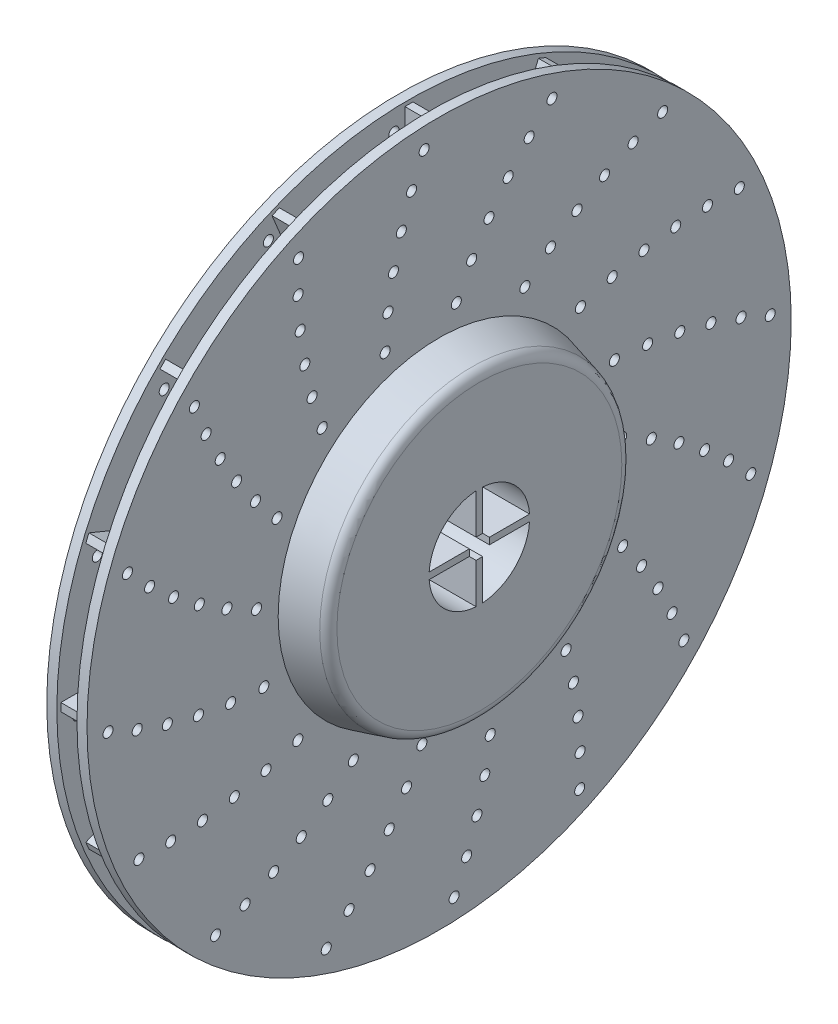
SolidWorks part; units mm, degrees
material "AISI 1020"
ref_plane "Ön Düzlem" through (0, 0, 0) normal (0, 0, 1) x (1, 0, 0)
ref_plane "Üst Düzlem" through (0, 0, 0) normal (0, 1, 0) x (1, 0, 0)
ref_plane "Sağ Düzlem" through (0, 0, 0) normal (1, 0, 0) x (0, 0, -1)
sketch "Çizim2" plane through (0, 0, 0) normal (1, 0, 0) x (0, 0, -1)
  line L0 (0.8201, 2.5) -> (0.8201, 12.4731)
  line L1 (12.4731, 0.8201) -> (2.5, 0.8201)
  line L2 (-0.8201, 12.4731) -> (-0.8201, 2.5)
  line L3 (-2.5, 0.8201) -> (-12.4731, 0.8201)
  line L4 (-12.4731, -0.8201) -> (-2.5, -0.8201)
  line L5 (-0.8201, -2.5) -> (-0.8201, -12.4731)
  line L6 (0.8201, -12.4731) -> (0.8201, -2.5)
  line L7 (2.5, -0.8201) -> (12.4731, -0.8201)
  line L8 (0, 0) -> (0.8201, 0.8201) construction
  line L9 (-0.8201, 2.5) -> (0.8201, 2.5)
  line L10 (-2.5, 0.8201) -> (-2.5, -0.8201)
  line L11 (-0.8201, -2.5) -> (0.8201, -2.5)
  line L12 (2.5, 0.8201) -> (2.5, -0.8201)
  line L13 (0, 0) -> (0.8201, -0.8201) construction
  arc A4 (-12.4731, 0.8201) -> (-12.4731, -0.8201) centre (0, 0) ccw
  arc A5 (-0.8201, -12.4731) -> (0.8201, -12.4731) centre (0, 0) ccw
  arc A6 (12.4731, -0.8201) -> (12.4731, 0.8201) centre (0, 0) ccw
  arc A7 (0.8201, 12.4731) -> (-0.8201, 12.4731) centre (0, 0) ccw
extrude "Yükseklik-Ekstrüzyon1" add sketch "Çizim2" along normal blind 30
sketch "Çizim3" plane through (0, 0, 0) normal (1, 0, 0) x (0, 0, -1)
  circle A0 centre (0, 0) radius 12.5
  circle A1 centre (0, 0) radius 25
  dimension "D1" = 25
  dimension "D2" = 50
extrude "Yükseklik-Ekstrüzyon2" add sketch "Çizim3" along normal blind 30
sketch "Çizim4" plane through (30, 0, 0) normal (1, 0, 0) x (0, 0, -1)
  circle A0 centre (0, 0) radius 25
  circle A1 centre (0, 0) radius 87.5
  dimension "D1" = 175
extrude "Yükseklik-Ekstrüzyon5" add sketch "Çizim4" against normal blind 10 from offset 10 offset against normal yes
ref_plane "Düzlem1" through (15, 0, 0) normal (1, 0, 0) x (0, 0, -1)
sketch "Çizim9" plane through (15, 0, 0) normal (1, 0, 0) x (0, 0, -1)
  circle A0 centre (0, 0) radius 37.5
  circle A1 centre (0, 0) radius 87.5
  dimension "D1" = 75
extrude "Kes-Ekstrüzyon1" cut sketch "Çizim9" against normal mid plane 5
sketch "Çizim10" plane through (15, 0, 0) normal (1, 0, 0) x (0, 0, -1)
  line L0 (0, 37.5) -> (0, 85) construction
  line L1 (1, 37.4867) -> (1, 86.4942)
  line L2 (-1, 37.4867) -> (-1, 86.4942)
  line L5 (-2.5, 35.9131) -> (-2.5, 86.4639) construction
  line L6 (2.5, 35.9131) -> (2.5, 86.4639) construction
  line L7 (-1, 37.4867) -> (-1, 84.9941) construction
  line L8 (1, 37.4867) -> (1, 84.9941) construction
  line L9 (15.2694, 34.2505) -> (34.0238, 79.5276)
  line L10 (13.4216, 35.0158) -> (32.176, 80.2929)
  line L11 (14.3506, 34.6455) -> (32.5281, 78.5298) construction
  line L12 (27.2142, 25.8) -> (61.8678, 60.4535)
  line L13 (25.8, 27.2142) -> (60.4535, 61.8678)
  line L14 (26.5165, 26.5165) -> (60.1041, 60.1041) construction
  line L15 (35.0158, 13.4216) -> (80.2929, 32.176)
  line L16 (34.2505, 15.2694) -> (79.5276, 34.0238)
  line L17 (34.6455, 14.3506) -> (78.5298, 32.5281) construction
  line L18 (37.4867, -1) -> (86.4942, -1)
  line L19 (37.4867, 1) -> (86.4942, 1)
  line L20 (37.5, 0) -> (85, 0) construction
  line L21 (34.2505, -15.2694) -> (79.5276, -34.0238)
  line L22 (35.0158, -13.4216) -> (80.2929, -32.176)
  line L23 (34.6455, -14.3506) -> (78.5298, -32.5281) construction
  line L24 (25.8, -27.2142) -> (60.4535, -61.8678)
  line L25 (27.2142, -25.8) -> (61.8678, -60.4535)
  line L26 (26.5165, -26.5165) -> (60.1041, -60.1041) construction
  line L27 (13.4216, -35.0158) -> (32.176, -80.2929)
  line L28 (15.2694, -34.2505) -> (34.0238, -79.5276)
  line L29 (14.3506, -34.6455) -> (32.5281, -78.5298) construction
  line L30 (-1, -37.4867) -> (-1, -86.4942)
  line L31 (1, -37.4867) -> (1, -86.4942)
  line L32 (0, -37.5) -> (0, -85) construction
  line L33 (-15.2694, -34.2505) -> (-34.0238, -79.5276)
  line L34 (-13.4216, -35.0158) -> (-32.176, -80.2929)
  line L35 (-14.3506, -34.6455) -> (-32.5281, -78.5298) construction
  line L36 (-27.2142, -25.8) -> (-61.8678, -60.4535)
  line L37 (-25.8, -27.2142) -> (-60.4535, -61.8678)
  line L38 (-26.5165, -26.5165) -> (-60.1041, -60.1041) construction
  line L39 (-35.0158, -13.4216) -> (-80.2929, -32.176)
  line L40 (-34.2505, -15.2694) -> (-79.5276, -34.0238)
  line L41 (-34.6455, -14.3506) -> (-78.5298, -32.5281) construction
  line L42 (-37.4867, 1) -> (-86.4942, 1)
  line L43 (-37.4867, -1) -> (-86.4942, -1)
  line L44 (-37.5, 0) -> (-85, 0) construction
  line L45 (-34.2505, 15.2694) -> (-79.5276, 34.0238)
  line L46 (-35.0158, 13.4216) -> (-80.2929, 32.176)
  line L47 (-34.6455, 14.3506) -> (-78.5298, 32.5281) construction
  line L48 (-25.8, 27.2142) -> (-60.4535, 61.8678)
  line L49 (-27.2142, 25.8) -> (-61.8678, 60.4535)
  line L50 (-26.5165, 26.5165) -> (-60.1041, 60.1041) construction
  line L51 (-13.4216, 35.0158) -> (-32.176, 80.2929)
  line L52 (-15.2694, 34.2505) -> (-34.0238, 79.5276)
  line L53 (-14.3506, 34.6455) -> (-32.5281, 78.5298) construction
  arc A0 (1, 37.4867) -> (-1, 37.4867) centre (0, 0) ccw
  arc A3 (1, 86.4942) -> (-1, 86.4942) centre (0, 0) ccw
  arc A5 (2.5, 35.9131) -> (-2.5, 35.9131) centre (0, 0) ccw construction
  arc A6 (1, 84.9941) -> (-1, 84.9941) centre (0, 0) ccw construction
  arc A7 (2.5, 86.4639) -> (-2.5, 86.4639) centre (0, 0) ccw construction
  arc A8 (15.2694, 34.2505) -> (13.4216, 35.0158) centre (0, 0) ccw
  arc A9 (34.0238, 79.5276) -> (32.176, 80.2929) centre (0, 0) ccw
  arc A10 (27.2142, 25.8) -> (25.8, 27.2142) centre (0, 0) ccw
  arc A11 (61.8678, 60.4535) -> (60.4535, 61.8678) centre (0, 0) ccw
  arc A12 (35.0158, 13.4216) -> (34.2505, 15.2694) centre (0, 0) ccw
  arc A13 (80.2929, 32.176) -> (79.5276, 34.0238) centre (0, 0) ccw
  arc A14 (37.4867, -1) -> (37.4867, 1) centre (0, 0) ccw
  arc A15 (86.4942, -1) -> (86.4942, 1) centre (0, 0) ccw
  arc A16 (34.2505, -15.2694) -> (35.0158, -13.4216) centre (0, 0) ccw
  arc A17 (79.5276, -34.0238) -> (80.2929, -32.176) centre (0, 0) ccw
  arc A18 (25.8, -27.2142) -> (27.2142, -25.8) centre (0, 0) ccw
  arc A19 (60.4535, -61.8678) -> (61.8678, -60.4535) centre (0, 0) ccw
  arc A20 (13.4216, -35.0158) -> (15.2694, -34.2505) centre (0, 0) ccw
  arc A21 (32.176, -80.2929) -> (34.0238, -79.5276) centre (0, 0) ccw
  arc A22 (-1, -37.4867) -> (1, -37.4867) centre (0, 0) ccw
  arc A23 (-1, -86.4942) -> (1, -86.4942) centre (0, 0) ccw
  arc A24 (-15.2694, -34.2505) -> (-13.4216, -35.0158) centre (0, 0) ccw
  arc A25 (-34.0238, -79.5276) -> (-32.176, -80.2929) centre (0, 0) ccw
  arc A26 (-27.2142, -25.8) -> (-25.8, -27.2142) centre (0, 0) ccw
  arc A27 (-61.8678, -60.4535) -> (-60.4535, -61.8678) centre (0, 0) ccw
  arc A28 (-35.0158, -13.4216) -> (-34.2505, -15.2694) centre (0, 0) ccw
  arc A29 (-80.2929, -32.176) -> (-79.5276, -34.0238) centre (0, 0) ccw
  arc A30 (-37.4867, 1) -> (-37.4867, -1) centre (0, 0) ccw
  arc A31 (-86.4942, 1) -> (-86.4942, -1) centre (0, 0) ccw
  arc A32 (-34.2505, 15.2694) -> (-35.0158, 13.4216) centre (0, 0) ccw
  arc A33 (-79.5276, 34.0238) -> (-80.2929, 32.176) centre (0, 0) ccw
  arc A34 (-25.8, 27.2142) -> (-27.2142, 25.8) centre (0, 0) ccw
  arc A35 (-60.4535, 61.8678) -> (-61.8678, 60.4535) centre (0, 0) ccw
  arc A36 (-13.4216, 35.0158) -> (-15.2694, 34.2505) centre (0, 0) ccw
  arc A37 (-32.176, 80.2929) -> (-34.0238, 79.5276) centre (0, 0) ccw
  point P84 (0, 0)
  dimension "D1" = 75
  dimension "D2" = 16
  dimension "D3" = 1
  dimension "D4" = 1.5
extrude "Yükseklik-Ekstrüzyon9" add sketch "Çizim10" along normal mid plane 5
sketch "Çizim14" plane through (15, 0, 0) normal (1, 0, 0) x (0, 0, -1)
  line L0 (-27.2142, -25.8) -> (-80.4344, -34.4465) construction
  circle A0 centre (0, 0) radius 37.5 construction
  circle A1 centre (0, 0) radius 87.5 construction
  arc A2 (-27.2142, -25.8) -> (-80.4344, -34.4465) centre (-69.2669, 64.928) cw construction
  circle A3 centre (-35.1106, -29.0579) radius 1.25
  circle A4 centre (-43.0071, -31.5625) radius 1.25
  circle A5 centre (-50.9036, -33.3715) radius 1.25
  circle A6 centre (-58.8, -34.5227) radius 1.25
  circle A7 centre (-66.6965, -35.0389) radius 1.25
  circle A8 centre (-74.593, -34.9301) radius 1.25
  circle A9 centre (-82.2821, -3.7257) radius 1.25
  circle A10 centre (-75.0284, -6.8481) radius 1.25
  circle A11 centre (-67.5354, -9.393) radius 1.25
  circle A12 centre (-59.7995, -11.3513) radius 1.25
  circle A13 centre (-51.8118, -12.7019) radius 1.25
  circle A14 centre (-43.558, -13.4097) radius 1.25
  circle A15 centre (-77.4445, 28.0459) radius 1.25
  circle A16 centre (-71.9378, 22.3853) radius 1.25
  circle A17 centre (-65.9891, 17.1667) radius 1.25
  circle A18 centre (-59.5915, 12.3971) radius 1.25
  circle A19 centre (-52.7287, 8.0925) radius 1.25
  circle A20 centre (-45.374, 4.28) radius 1.25
  circle A21 centre (-60.8167, 55.5478) radius 1.25
  circle A22 centre (-57.8954, 48.2107) radius 1.25
  circle A23 centre (-54.3966, 41.1129) radius 1.25
  circle A24 centre (-50.3112, 34.2581) radius 1.25
  circle A25 centre (-45.6181, 27.6549) radius 1.25
  circle A26 centre (-40.2822, 21.318) radius 1.25
  circle A27 centre (-34.9301, 74.593) radius 1.25
  circle A28 centre (-35.0389, 66.6965) radius 1.25
  circle A29 centre (-34.5227, 58.8) radius 1.25
  circle A30 centre (-33.3715, 50.9036) radius 1.25
  circle A31 centre (-31.5625, 43.0071) radius 1.25
  circle A32 centre (-29.0579, 35.1106) radius 1.25
  circle A33 centre (-3.7257, 82.2821) radius 1.25
  circle A34 centre (-6.8481, 75.0284) radius 1.25
  circle A35 centre (-9.393, 67.5354) radius 1.25
  circle A36 centre (-11.3513, 59.7995) radius 1.25
  circle A37 centre (-12.7019, 51.8118) radius 1.25
  circle A38 centre (-13.4097, 43.558) radius 1.25
  circle A39 centre (28.0459, 77.4445) radius 1.25
  circle A40 centre (22.3853, 71.9378) radius 1.25
  circle A41 centre (17.1667, 65.9891) radius 1.25
  circle A42 centre (12.3971, 59.5915) radius 1.25
  circle A43 centre (8.0925, 52.7287) radius 1.25
  circle A44 centre (4.28, 45.374) radius 1.25
  circle A45 centre (55.5478, 60.8167) radius 1.25
  circle A46 centre (48.2107, 57.8954) radius 1.25
  circle A47 centre (41.1129, 54.3966) radius 1.25
  circle A48 centre (34.2581, 50.3112) radius 1.25
  circle A49 centre (27.6549, 45.6181) radius 1.25
  circle A50 centre (21.318, 40.2822) radius 1.25
  circle A51 centre (74.593, 34.9301) radius 1.25
  circle A52 centre (66.6965, 35.0389) radius 1.25
  circle A53 centre (58.8, 34.5227) radius 1.25
  circle A54 centre (50.9036, 33.3715) radius 1.25
  circle A55 centre (43.0071, 31.5625) radius 1.25
  circle A56 centre (35.1106, 29.0579) radius 1.25
  circle A57 centre (82.2821, 3.7257) radius 1.25
  circle A58 centre (75.0284, 6.8481) radius 1.25
  circle A59 centre (67.5354, 9.393) radius 1.25
  circle A60 centre (59.7995, 11.3513) radius 1.25
  circle A61 centre (51.8118, 12.7019) radius 1.25
  circle A62 centre (43.558, 13.4097) radius 1.25
  circle A63 centre (77.4445, -28.0459) radius 1.25
  circle A64 centre (71.9378, -22.3853) radius 1.25
  circle A65 centre (65.9891, -17.1667) radius 1.25
  circle A66 centre (59.5915, -12.3971) radius 1.25
  circle A67 centre (52.7287, -8.0925) radius 1.25
  circle A68 centre (45.374, -4.28) radius 1.25
  circle A69 centre (60.8167, -55.5478) radius 1.25
  circle A70 centre (57.8954, -48.2107) radius 1.25
  circle A71 centre (54.3966, -41.1129) radius 1.25
  circle A72 centre (50.3112, -34.2581) radius 1.25
  circle A73 centre (45.6181, -27.6549) radius 1.25
  circle A74 centre (40.2822, -21.318) radius 1.25
  circle A75 centre (34.9301, -74.593) radius 1.25
  circle A76 centre (35.0389, -66.6965) radius 1.25
  circle A77 centre (34.5227, -58.8) radius 1.25
  circle A78 centre (33.3715, -50.9036) radius 1.25
  circle A79 centre (31.5625, -43.0071) radius 1.25
  circle A80 centre (29.0579, -35.1106) radius 1.25
  circle A81 centre (3.7257, -82.2821) radius 1.25
  circle A82 centre (6.8481, -75.0284) radius 1.25
  circle A83 centre (9.393, -67.5354) radius 1.25
  circle A84 centre (11.3513, -59.7995) radius 1.25
  circle A85 centre (12.7019, -51.8118) radius 1.25
  circle A86 centre (13.4097, -43.558) radius 1.25
  circle A87 centre (-28.0459, -77.4445) radius 1.25
  circle A88 centre (-22.3853, -71.9378) radius 1.25
  circle A89 centre (-17.1667, -65.9891) radius 1.25
  circle A90 centre (-12.3971, -59.5915) radius 1.25
  circle A91 centre (-8.0925, -52.7287) radius 1.25
  circle A92 centre (-4.28, -45.374) radius 1.25
  circle A93 centre (-55.5478, -60.8167) radius 1.25
  circle A94 centre (-48.2107, -57.8954) radius 1.25
  circle A95 centre (-41.1129, -54.3966) radius 1.25
  circle A96 centre (-34.2581, -50.3112) radius 1.25
  circle A97 centre (-27.6549, -45.6181) radius 1.25
  circle A98 centre (-21.318, -40.2822) radius 1.25
  point P7 (-35.1106, -27.0829)
  point P9 (-43.0071, -28.3658)
  point P10 (-50.9036, -29.6487)
  point P12 (-58.8, -30.9316)
  point P13 (-66.6965, -32.2145)
  point P23 (-74.593, -33.4974)
  point P208 (0, 0)
  dimension "D1" = 100
  dimension "D2" = 8
  dimension "D7" = 2.5
  dimension "D8" = 2.5
  dimension "D9" = 2.5
  dimension "D10" = 2.5
  dimension "D11" = 2.5
  dimension "D13" = 2.5
  dimension "D14" = 16
  dimension "D3" = 8
  dimension "D4" = 8
  dimension "D5" = 8
  dimension "D6" = 8
  dimension "D12" = 8
extrude "Kes-Ekstrüzyon2" cut sketch "Çizim14" against normal mid plane 10
sketch "Çizim18" plane through (0, 0, 0) normal (0, 0, 1) x (1, 0, 0)
  line L0 (0, 25) -> (0, 35.4022)
  line L1 (10, 25) -> (10, 40)
  line L2 (10, 40) -> (1.853, 37.817)
  line L3 (0, 0) -> (0, 40) construction
  line L4 (0, 25) -> (10, 25)
  line L5 (0, 0) -> (15, 0) construction
  line L6 (10, 0) -> (10, 40) construction
  line L8 (15, 0) -> (15, 91.5897) construction
  line L9 (30, 25) -> (20, 25)
  line L10 (20, 40) -> (28.147, 37.817)
  line L11 (20, 25) -> (20, 40)
  line L12 (30, 25) -> (30, 35.4022)
  arc A0 (0, 35.4022) -> (1.853, 37.817) centre (2.5, 35.4022) cw
  arc A1 (30, 35.4022) -> (28.147, 37.817) centre (27.5, 35.4022) ccw
  dimension "D1" = 2.5
  dimension "D3" = 75
  dimension "D4" = 15
  dimension "D2" = 10
revolve "Döndür3" add sketch "Çizim18" angle 360 about L5
